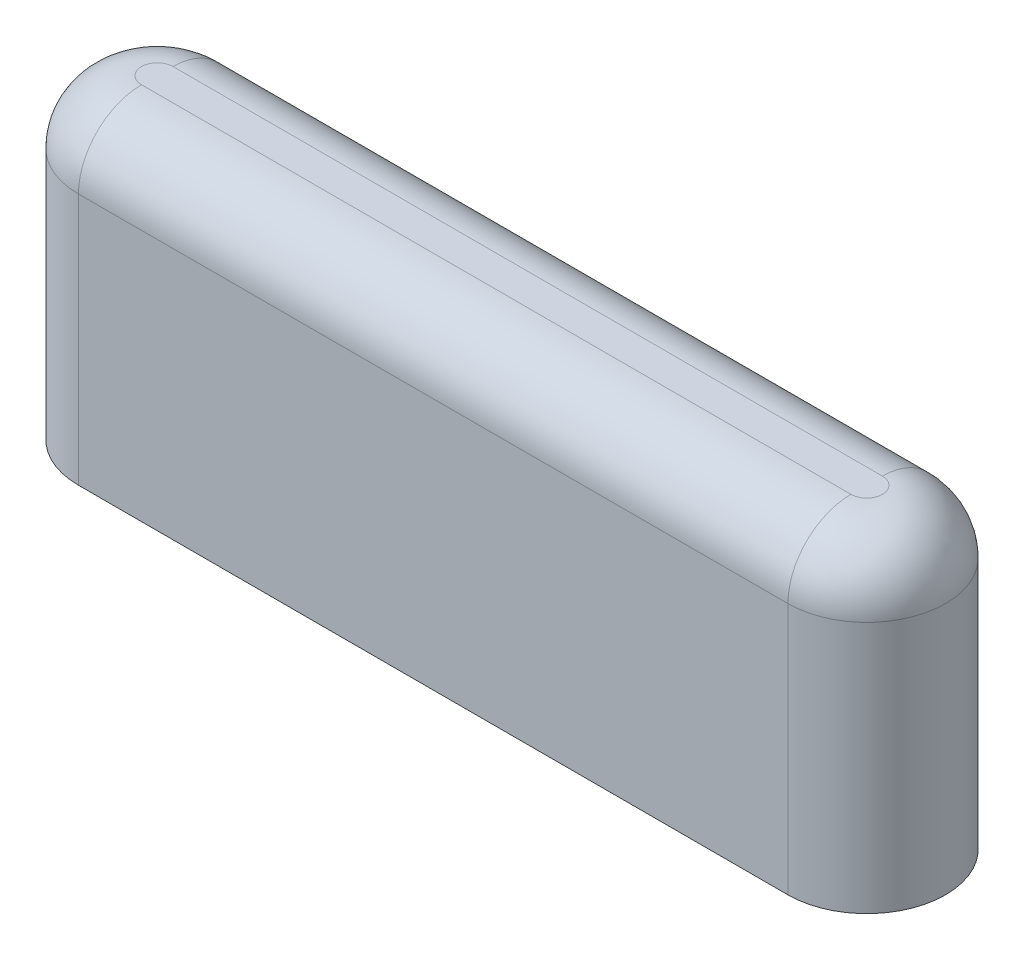
SolidWorks part; units mm, degrees
material "1060 Alloy"
ref_plane "Front Plane" through (0, 0, 0) normal (0, 0, 1) x (1, 0, 0)
ref_plane "Top Plane" through (0, 0, 0) normal (0, 1, 0) x (1, 0, 0)
ref_plane "Right Plane" through (0, 0, 0) normal (1, 0, 0) x (0, 0, -1)
sketch "Sketch1" plane through (0, 0, 0) normal (0, 1, 0) x (1, 0, 0)
  line L1 (22.5, -5) -> (-22.5, -5)
  line L2 (22.5, -5) -> (22.5, 5) construction
  line L3 (22.5, 5) -> (-22.5, 5)
  line L4 (-22.5, -5) -> (-22.5, 5) construction
  line L5 (22.5, -5) -> (-22.5, 5) construction
  line L6 (22.5, 5) -> (-22.5, -5) construction
  arc A0 (-22.5, -5) -> (-22.5, 5) centre (-22.5, 0) cw
  arc A1 (22.5, -5) -> (22.5, 5) centre (22.5, 0) ccw
  point P0 (0, 0)
  point P10 (0, 0)
  point P11 (0, 0)
  dimension "D1" = 45
  dimension "D2" = 10
extrude "Boss-Extrude1" add sketch "Sketch1" along normal blind 20 contours L1 A0 L3 A1
fillet "Fillet1" radius 4 4 edges at (27.5, 20, 0) (0, 20, -5) (-27.5, 20, 0) (0, 20, 5)
sketch "Sketch2" plane through (0, 0, 0) normal (0, -1, 0) x (1, 0, 0)
  circle A0 centre (-22.5, 0) radius 2.75
  dimension "D1" = 5.5
extrude "Cut-Extrude1" cut sketch "Sketch2" against normal blind 1.5
pattern_linear "LPattern1" count 2 spacing 30 along (1, 0, 0) of "Cut-Extrude1"
